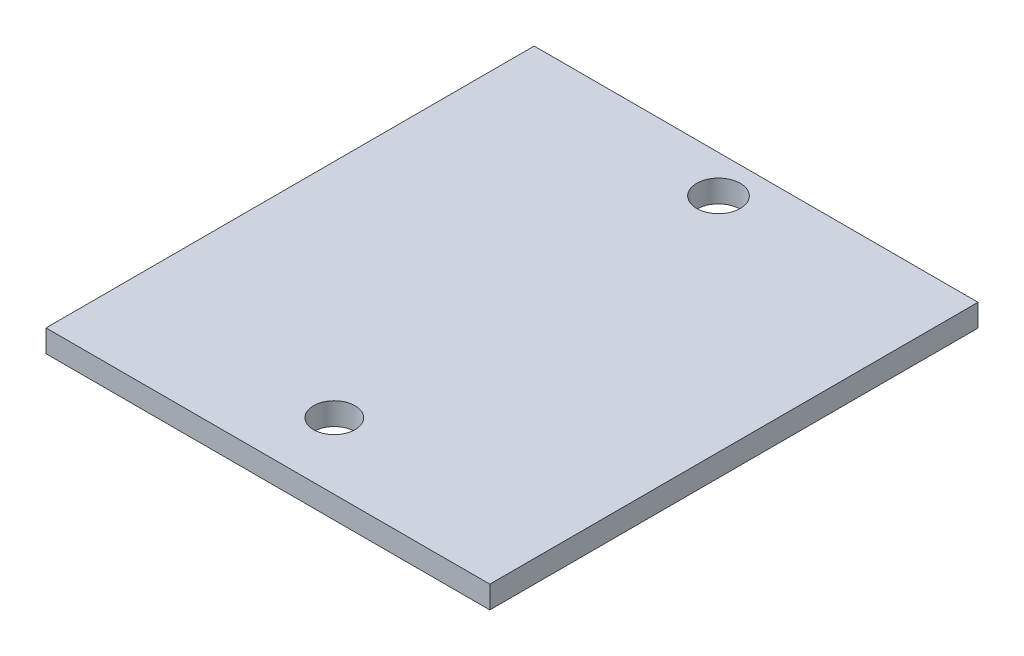
SolidWorks part; units mm, degrees
ref_plane "Front Plane" through (0, 0, 0) normal (0, 0, 1) x (1, 0, 0)
ref_plane "Top Plane" through (0, 0, 0) normal (0, 1, 0) x (1, 0, 0)
ref_plane "Right Plane" through (0, 0, 0) normal (1, 0, 0) x (0, 0, -1)
sketch "Sketch1" plane through (0, 0, 0) normal (0, 1, 0) x (1, 0, 0)
  line L1 (-31.75, -34.925) -> (31.75, -34.925)
  line L2 (-31.75, -34.925) -> (-31.75, 34.925)
  line L3 (-31.75, 34.925) -> (31.75, 34.925)
  line L4 (31.75, -34.925) -> (31.75, 34.925)
  line L5 (-31.75, -34.925) -> (31.75, 34.925) construction
  line L6 (-31.75, 34.925) -> (31.75, -34.925) construction
  circle A0 centre (0, -25.4274) radius 2.9734
  circle A1 centre (0, 29.5454) radius 3.1203
  point P0 (0, 0)
  dimension "D1" = 63.5
  dimension "D2" = 69.85
extrude "Boss-Extrude1" add sketch "Sketch1" along normal blind 3.2004
